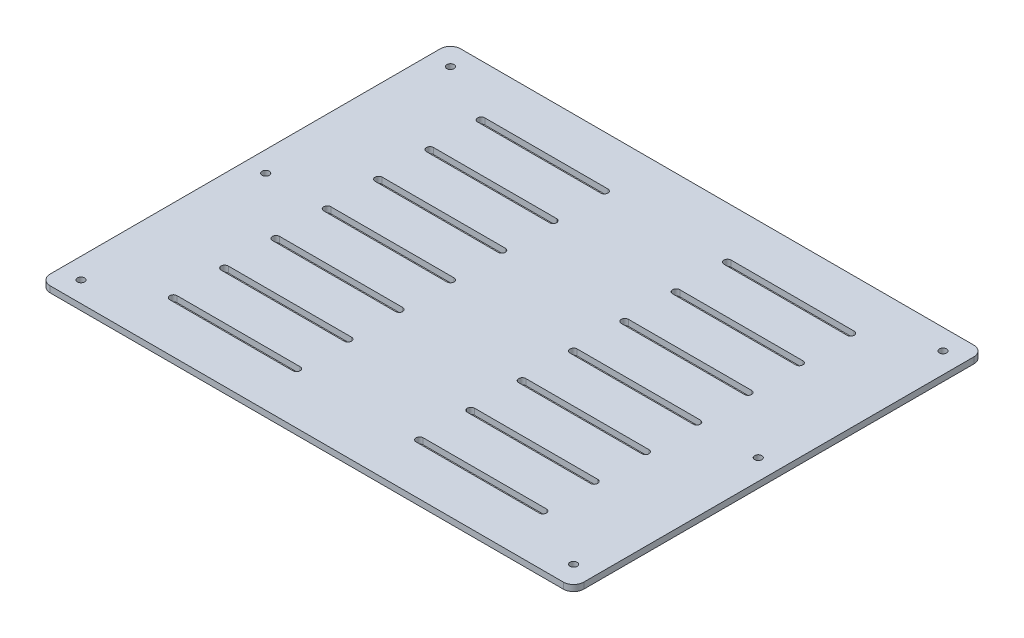
SolidWorks part; units mm, degrees
ref_plane "前视基准面" through (0, 0, 0) normal (0, 0, 1) x (1, 0, 0)
ref_plane "上视基准面" through (0, 0, 0) normal (0, 1, 0) x (1, 0, 0)
ref_plane "右视基准面" through (0, 0, 0) normal (1, 0, 0) x (0, 0, -1)
other "Configuration Table"
sketch "草图1" plane through (0, 0, 0) normal (0, 1, 0) x (1, 0, 0)
  line L1 (-130, -100) -> (130, -100)
  line L2 (-130, -100) -> (-130, 100)
  line L3 (-130, 100) -> (130, 100)
  line L4 (130, -100) -> (130, 100)
  line L5 (-130, -100) -> (130, 100) construction
  line L6 (-130, 100) -> (130, -100) construction
  point P0 (0, 0)
  dimension "D1" = 260
  dimension "D2" = 200
extrude "凸台-拉伸1" add sketch "草图1" along normal blind 3
fillet "圆角1" radius 5 4 edges at (-130, 1.5, 100) (-130, 1.5, -100) (130, 1.5, 100) (130, 1.5, -100)
sketch "草图2" plane through (0, 0, 0) normal (0, -1, 0) x (1, 0, 0)
  line L0 (0, 0) -> (50000, 0) construction
  line L1 (130, 95) -> (130, -95) construction
  line L2 (-125, 100) -> (125, 100) construction
  line L3 (0, 0) -> (0, 50000) construction
  circle A0 centre (120, 90) radius 1.75
  circle A1 centre (120, -90) radius 1.75
  circle A2 centre (-120, -90) radius 1.75
  circle A3 centre (-120, 90) radius 1.75
  circle A4 centre (-120, 0) radius 1.75
  circle A5 centre (120, 0) radius 1.75
  dimension "D1" = 10
  dimension "D2" = 3.5
  dimension "D3" = 10
  dimension "D4" = 3.5
extrude "切除-拉伸1" cut sketch "草图2" against normal blind 10
sketch "草图3" plane through (0, 3, 0) normal (0, 1, 0) x (1, 0, 0)
  line L0 (0, 0) -> (-50000, 0) construction
  line L1 (0, 0) -> (0, -50000) construction
  line L2 (-90, -75) -> (-30, -75) construction
  line L3 (-90, -73.25) -> (-30, -73.25)
  line L4 (-90, -76.75) -> (-30, -76.75)
  line L5 (-130, 95) -> (-130, -95) construction
  line L6 (-125, -100) -> (125, -100) construction
  line L7 (-90, -50) -> (-30, -50) construction
  line L8 (-90, -48.25) -> (-30, -48.25)
  line L9 (-90, -51.75) -> (-30, -51.75)
  line L10 (-90, -25) -> (-30, -25) construction
  line L11 (-90, -23.25) -> (-30, -23.25)
  line L12 (-90, -26.75) -> (-30, -26.75)
  line L13 (-90, 0) -> (-30, 0) construction
  line L14 (-90, 1.75) -> (-30, 1.75)
  line L15 (-90, -1.75) -> (-30, -1.75)
  line L16 (-90, 25) -> (-30, 25) construction
  line L17 (-90, 23.25) -> (-30, 23.25)
  line L18 (-90, 26.75) -> (-30, 26.75)
  line L19 (-90, 50) -> (-30, 50) construction
  line L20 (-90, 48.25) -> (-30, 48.25)
  line L21 (-90, 51.75) -> (-30, 51.75)
  line L22 (-90, 75) -> (-30, 75) construction
  line L23 (-90, 73.25) -> (-30, 73.25)
  line L24 (-90, 76.75) -> (-30, 76.75)
  line L25 (90, 75) -> (30, 75) construction
  line L26 (90, 73.25) -> (30, 73.25)
  line L27 (90, 76.75) -> (30, 76.75)
  line L28 (90, 50) -> (30, 50) construction
  line L29 (90, 48.25) -> (30, 48.25)
  line L30 (90, 51.75) -> (30, 51.75)
  line L31 (90, 25) -> (30, 25) construction
  line L32 (90, 23.25) -> (30, 23.25)
  line L33 (90, 26.75) -> (30, 26.75)
  line L34 (90, 0) -> (30, 0) construction
  line L35 (90, 1.75) -> (30, 1.75)
  line L36 (90, -1.75) -> (30, -1.75)
  line L37 (90, -25) -> (30, -25) construction
  line L38 (90, -23.25) -> (30, -23.25)
  line L39 (90, -26.75) -> (30, -26.75)
  line L40 (90, -50) -> (30, -50) construction
  line L41 (90, -48.25) -> (30, -48.25)
  line L42 (90, -51.75) -> (30, -51.75)
  line L43 (90, -75) -> (30, -75) construction
  line L44 (90, -73.25) -> (30, -73.25)
  line L45 (90, -76.75) -> (30, -76.75)
  arc A1 (-90, -73.25) -> (-90, -76.75) centre (-90, -75) ccw
  arc A2 (-30, -76.75) -> (-30, -73.25) centre (-30, -75) ccw
  arc A3 (-90, -48.25) -> (-90, -51.75) centre (-90, -50) ccw
  arc A4 (-30, -51.75) -> (-30, -48.25) centre (-30, -50) ccw
  arc A5 (-90, -23.25) -> (-90, -26.75) centre (-90, -25) ccw
  arc A6 (-30, -26.75) -> (-30, -23.25) centre (-30, -25) ccw
  arc A7 (-90, 1.75) -> (-90, -1.75) centre (-90, 0) ccw
  arc A8 (-30, -1.75) -> (-30, 1.75) centre (-30, 0) ccw
  arc A9 (-90, 23.25) -> (-90, 26.75) centre (-90, 25) cw
  arc A10 (-30, 26.75) -> (-30, 23.25) centre (-30, 25) cw
  arc A11 (-90, 48.25) -> (-90, 51.75) centre (-90, 50) cw
  arc A12 (-30, 51.75) -> (-30, 48.25) centre (-30, 50) cw
  arc A13 (-90, 73.25) -> (-90, 76.75) centre (-90, 75) cw
  arc A14 (-30, 76.75) -> (-30, 73.25) centre (-30, 75) cw
  arc A15 (90, 73.25) -> (90, 76.75) centre (90, 75) ccw
  arc A16 (30, 76.75) -> (30, 73.25) centre (30, 75) ccw
  arc A17 (90, 48.25) -> (90, 51.75) centre (90, 50) ccw
  arc A18 (30, 51.75) -> (30, 48.25) centre (30, 50) ccw
  arc A19 (90, 23.25) -> (90, 26.75) centre (90, 25) ccw
  arc A20 (30, 26.75) -> (30, 23.25) centre (30, 25) ccw
  arc A21 (90, 1.75) -> (90, -1.75) centre (90, 0) cw
  arc A22 (30, -1.75) -> (30, 1.75) centre (30, 0) cw
  arc A23 (90, -23.25) -> (90, -26.75) centre (90, -25) cw
  arc A24 (30, -26.75) -> (30, -23.25) centre (30, -25) cw
  arc A25 (90, -48.25) -> (90, -51.75) centre (90, -50) cw
  arc A26 (30, -51.75) -> (30, -48.25) centre (30, -50) cw
  arc A27 (90, -73.25) -> (90, -76.75) centre (90, -75) cw
  arc A28 (30, -76.75) -> (30, -73.25) centre (30, -75) cw
  point P7 (-60, -75)
  point P19 (-60, -50)
  point P26 (-60, -25)
  point P33 (-60, 0)
  point P39 (-60, 25)
  point P46 (-60, 50)
  point P53 (-60, 75)
  point P60 (60, 75)
  point P67 (60, 50)
  point P74 (60, 25)
  point P81 (60, 0)
  point P88 (60, -25)
  point P95 (60, -50)
  point P102 (60, -75)
  dimension "D1" = 60
  dimension "D3" = 1.75
  dimension "D2" = 40
  dimension "D4" = 25
  dimension "D5" = 4
extrude "切除-拉伸2" cut sketch "草图3" against normal blind 10
